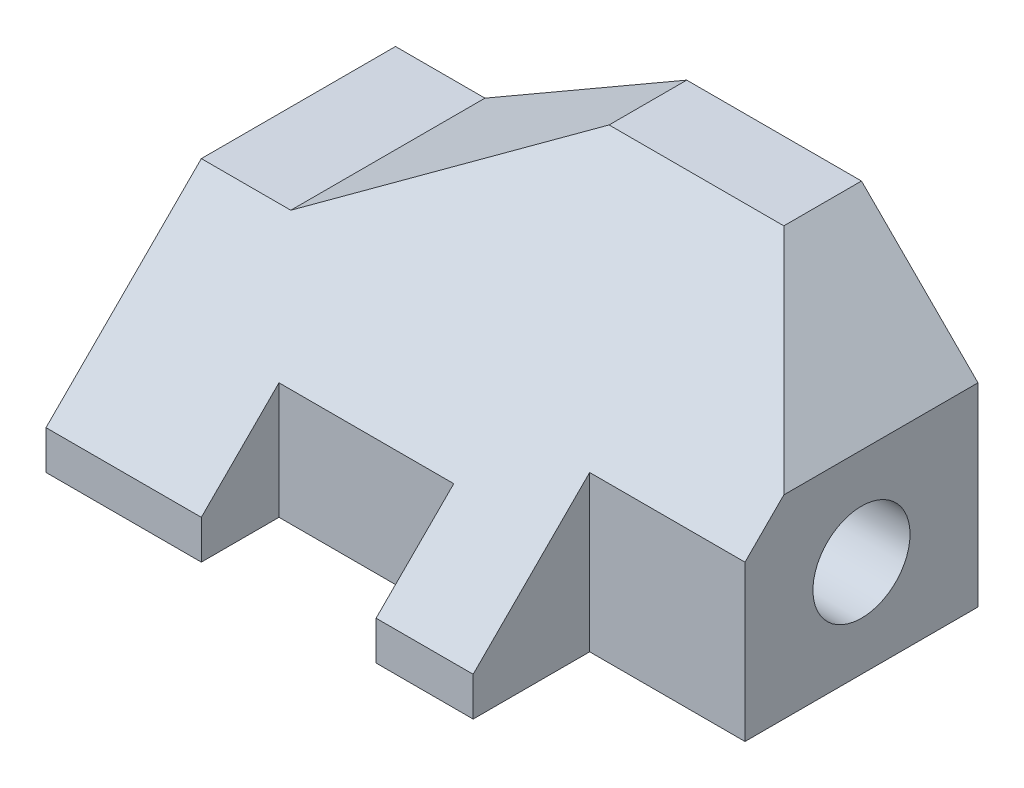
SolidWorks part; units mm, degrees
ref_plane "Plan de face" through (0, 0, 0) normal (0, 0, 1) x (1, 0, 0)
ref_plane "Plan de dessus" through (0, 0, 0) normal (0, 1, 0) x (1, 0, 0)
ref_plane "Plan de droite" through (0, 0, 0) normal (1, 0, 0) x (0, 0, -1)
sketch "Esquisse1" plane through (0, 0, 0) normal (0, 1, 0) x (1, 0, 0)
  line L1 (-47.625, -28.575) -> (47.625, -28.575)
  line L2 (-47.625, -28.575) -> (-47.625, 28.575)
  line L3 (-47.625, 28.575) -> (47.625, 28.575)
  line L4 (47.625, -28.575) -> (47.625, 28.575)
  line L5 (-47.625, -28.575) -> (47.625, 28.575) construction
  line L6 (-47.625, 28.575) -> (47.625, -28.575) construction
  point P0 (0, 0)
  dimension "D1" = 95.25
  dimension "D2" = 57.15
extrude "Creation forme départ" add sketch "Esquisse1" along normal blind 50.8
sketch "Esquisse3" plane through (0, 0, 28.575) normal (0, 0, 1) x (1, 0, 0)
  line L0 (47.625, 50.8) -> (28.575, 50.8)
  line L1 (-47.625, 50.8) -> (47.625, 50.8) construction
  line L2 (28.575, 50.8) -> (47.625, 31.75)
  line L3 (47.625, 50.8) -> (47.625, 0) construction
  line L4 (47.625, 31.75) -> (47.625, 50.8)
  line L6 (0, 50.8) -> (-32.9956, 31.75)
  line L7 (-32.9956, 31.75) -> (-47.625, 31.75)
  line L8 (-47.625, 50.8) -> (-47.625, 0) construction
  line L9 (-47.625, 31.75) -> (-47.625, 50.8)
  line L10 (-47.625, 50.8) -> (0, 50.8)
  dimension "D1" = 19.05
  dimension "D2" = 45
  dimension "D4" = 30
  dimension "D5" = 19.05
extrude "Enleve coins" cut sketch "Esquisse3" against normal blind 127
sketch "Esquisse4" plane through (47.625, 0, 0) normal (1, 0, 0) x (0, 0, -1)
  line L0 (15.875, 50.8) -> (-28.575, 50.8)
  line L1 (-28.575, 50.8) -> (28.575, 50.8) construction
  line L2 (15.875, 50.8) -> (-28.575, 6.35)
  line L3 (-28.575, 31.75) -> (-28.575, 0) construction
  line L4 (-28.575, 50.8) -> (-28.575, 6.35)
  dimension "D2" = 45
extrude "45 degree" cut sketch "Esquisse4" against normal blind 127
sketch "Esquisse5" plane through (0, 0, 0) normal (0, -1, 0) x (1, 0, 0)
  line L0 (47.625, 28.575) -> (22.225, 28.575)
  line L1 (-47.625, 28.575) -> (47.625, 28.575) construction
  line L2 (22.225, 28.575) -> (22.225, 9.525)
  line L3 (22.225, 9.525) -> (47.625, 9.525)
  line L4 (47.625, 28.575) -> (47.625, -28.575) construction
  line L5 (47.625, 9.525) -> (47.625, 28.575)
  line L6 (-47.625, 28.575) -> (-22.225, 28.575)
  line L7 (6.35, 28.575) -> (6.35, 15.875)
  line L8 (6.35, 15.875) -> (-22.225, 15.875)
  line L9 (-22.225, 15.875) -> (-22.225, 28.575)
  line L10 (-22.225, 28.575) -> (6.35, 28.575)
  line M8 (47.625, -28.575) -> (47.625, 28.575)
  line M9 (47.625, 28.575) -> (-47.625, 28.575)
  dimension "D1" = 25.4
  dimension "D2" = 19.05
  dimension "D3" = 25.4
  dimension "D4" = 28.575
  dimension "D5" = 12.7
extrude "Cubes de cote" cut sketch "Esquisse5" against normal blind 127 contours L2 L3 M8 M9 | L9 L8 L7 M9
hole_wizard "Percage" positions "Esquisse10" profile "Esquisse9" hole size "5/8" standard "Ansi Inch"
sketch "Esquisse10" plane through (47.625, 0, 0) normal (1, 0, 0) x (0, 0, -1)
  line L0 (28.575, 31.75) -> (28.575, 0) construction
  line L1 (-9.525, 0) -> (28.575, 0) construction
  point P0 (9.525, 15.875)
  dimension "D1" = 19.05
  dimension "D2" = 15.875
sketch "Esquisse9" plane through (47.625, 15.875, -9.525) normal (0, 1, 0) x (0, 0, -1)
  line L0 (0, 0) -> (0, 36.5193)
  line L1 (0, 36.5193) -> (7.9375, 31.75)
  line L2 (7.9375, 31.75) -> (7.9375, 0)
  line L5 (7.9375, 0) -> (0, 0)
  line L10 (0, 36.5193) -> (-7.9375, 31.75) construction
  line L11 (0, -6.35) -> (0, 107.95) construction
  dimension "Diamètre du perçage" = 15.875
  dimension "Profondeur du perçage" = 31.75
  dimension "Angle de pointe" = 118
